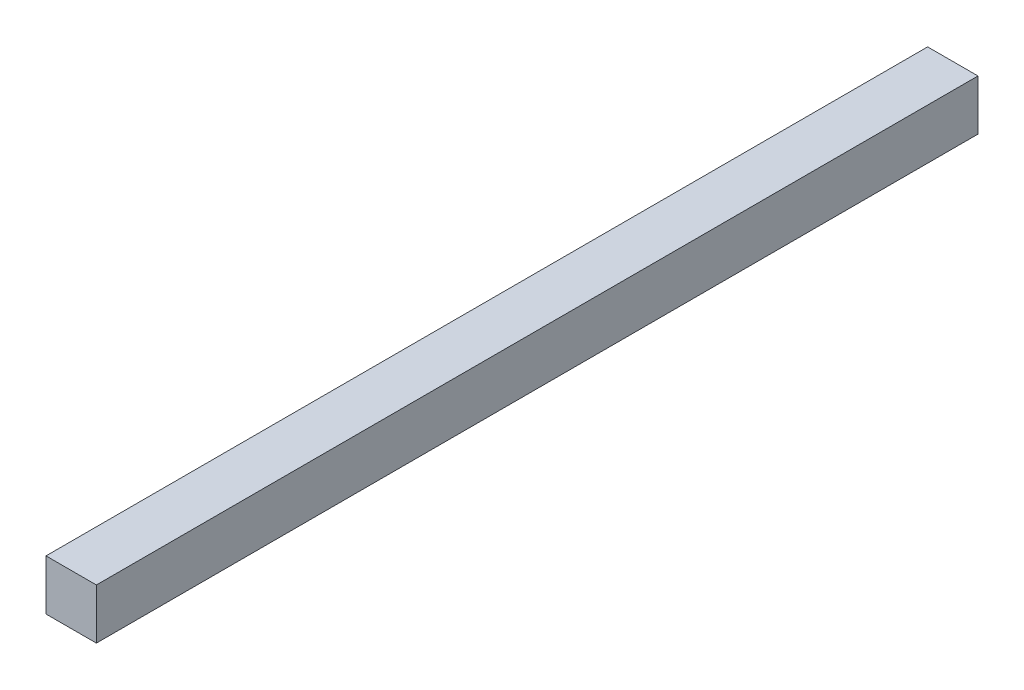
SolidWorks part; units mm, degrees
ref_plane "前基準面" through (0, 0, 0) normal (0, 0, 1) x (1, 0, 0)
ref_plane "上基準面" through (0, 0, 0) normal (0, 1, 0) x (1, 0, 0)
ref_plane "右基準面" through (0, 0, 0) normal (1, 0, 0) x (0, 0, -1)
sketch "草圖1" plane through (0, 0, 0) normal (0, 0, 1) x (1, 0, 0)
  line L1 (-10, 10) -> (10, 10)
  line L2 (-10, 10) -> (-10, -10)
  line L3 (-10, -10) -> (10, -10)
  line L4 (10, 10) -> (10, -10)
  point P4 (0, 10)
  point P6 (-10, 0)
  dimension "D1" = 20
  dimension "D2" = 20
extrude "填料-伸長1" add sketch "草圖1" along normal blind 350
